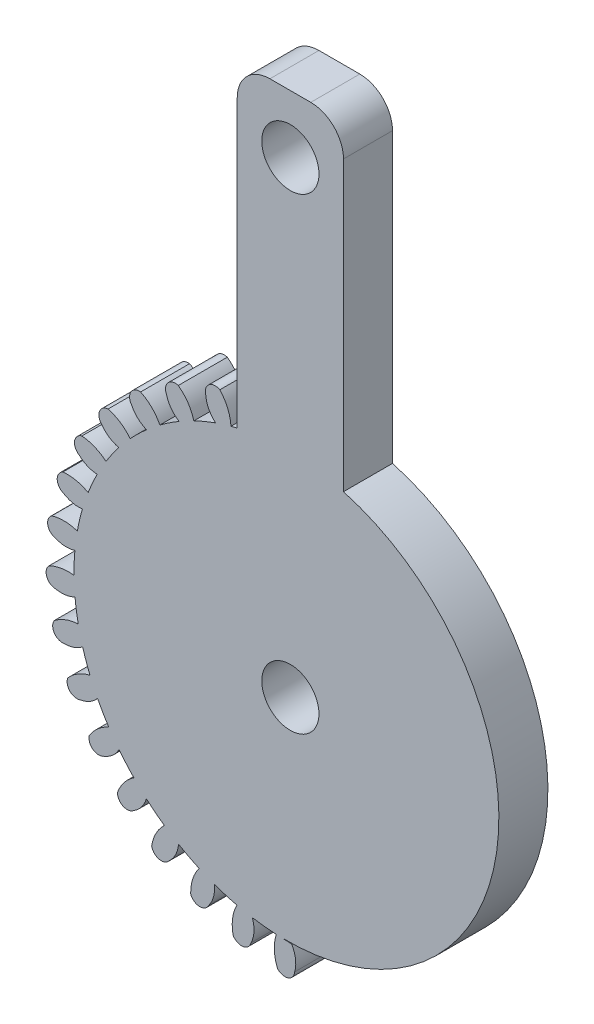
SolidWorks part; units mm, degrees
ref_plane "Front Plane" through (0, 0, 0) normal (0, 0, 1) x (1, 0, 0)
ref_plane "Top Plane" through (0, 0, 0) normal (0, 1, 0) x (1, 0, 0)
ref_plane "Right Plane" through (0, 0, 0) normal (1, 0, 0) x (0, 0, -1)
ref_plane "Plane1" through (0, 0, 5) normal (0, 0, 1) x (1, 0, 0)
ref_plane "Plane3" through (0, 0, 3) normal (0, 0, 1) x (1, 0, 0)
sketch "Sketch1" plane through (0, 0, 5) normal (0, 0, 1) x (1, 0, 0)
  circle A0 centre (0, 20.9252) radius 3.9726
  circle A1 centre (0, 20.9252) radius 5
  dimension "D1" = 10
sketch "Sketch5" plane through (0, 0, 3) normal (0, 0, 1) x (1, 0, 0)
  circle A0 centre (0, 20.9252) radius 13
extrude "Boss-Extrude3" add sketch "Sketch5" along normal blind 3 contours A0
sketch "Sketch6" plane through (0, 0, 3) normal (0, 0, 1) x (1, 0, 0)
  line L1 (-3.01, 33.0817) -> (3.49, 33.0817)
  line L2 (-3.01, 33.0817) -> (-3.01, 53.0817)
  line L3 (-3.01, 53.0817) -> (3.49, 53.0817)
  line L4 (3.49, 33.0817) -> (3.49, 53.0817)
  dimension "D1" = 20
  dimension "D2" = 6.5
extrude "Boss-Extrude4" add sketch "Sketch6" along normal up to surface (3 mm away) up to face at (13, 20.9252, 6)
sketch "Sketch8" plane through (0, 0, 3) normal (0, 0, 1) x (1, 0, 0)
  line L0 (-4.296, 33.1462) -> (-3.39, 33.4105)
  line L1 (0.24, 53.0817) -> (0.24, -3.388) construction
  line L2 (3.49, 53.0817) -> (-3.01, 53.0817) construction
  line L3 (13, 20.9252) -> (-7.0281, 20.9252) construction
  line L4 (-6.4797, 32.0955) -> (-5.6382, 32.5229)
  line L5 (-8.4311, 30.6587) -> (-7.6833, 31.2345)
  line L6 (-10.0829, 28.8855) -> (-9.4546, 29.5898)
  line L7 (-11.3779, 26.8373) -> (-10.8908, 27.6456)
  line L8 (-12.2715, 24.5847) -> (-11.9424, 25.4693)
  line L9 (-12.7326, 22.2057) -> (-12.573, 23.1358)
  line L10 (-12.7455, 19.7824) -> (-12.7607, 20.726)
  line L11 (-12.3095, 17.3986) -> (-12.4992, 18.3231)
  line L12 (-11.4399, 15.1367) -> (-11.7974, 16.0101)
  line L13 (-10.1667, 13.0748) -> (-10.6797, 13.867)
  line L14 (-8.5338, 11.2842) -> (-9.1845, 11.9678)
  line L15 (-6.5977, 9.8268) -> (-7.3637, 10.3781)
  line L16 (-4.4253, 8.753) -> (-5.2801, 9.1529)
  line L17 (-2.0916, 8.0998) -> (-3.0057, 8.3346)
  line L18 (0.3226, 7.8899) -> (-0.6192, 7.9514)
  arc A0 (-3.39, 33.4105) -> (-4.0758, 35.0663) centre (-5.9543, 33.3183) ccw
  arc A1 (-5.6382, 32.5229) -> (-6.6186, 34.0231) centre (-8.1411, 31.9576) ccw
  arc A2 (-4.0758, 35.0663) -> (-4.9399, 34.3825) centre (-4.3614, 34.5393) ccw
  arc A3 (-4.9399, 34.3825) -> (-4.296, 33.1462) centre (-3.1926, 34.5068) ccw
  arc A4 (-3.01, 33.572) -> (3.49, 33.448) centre (0, 20.9252) ccw construction
  arc A5 (-6.6186, 34.0231) -> (-7.3413, 33.1912) centre (-6.8018, 33.4524) ccw
  arc A6 (-7.3413, 33.1912) -> (-6.4797, 32.0955) centre (-5.6471, 33.6368) ccw
  arc A7 (-7.6833, 31.2345) -> (-8.9245, 32.5273) centre (-10.0383, 30.2157) ccw
  arc A8 (-8.9245, 32.5273) -> (-9.4806, 31.576) centre (-8.9988, 31.9325) ccw
  arc A9 (-9.4806, 31.576) -> (-8.4311, 30.6587) centre (-7.8982, 32.3274) ccw
  arc A10 (-9.4546, 29.5898) -> (-10.9136, 30.6305) centre (-11.5804, 28.1527) ccw
  arc A11 (-10.9136, 30.6305) -> (-11.2841, 29.5927) centre (-10.8765, 30.0323) ccw
  arc A12 (-11.2841, 29.5927) -> (-10.0829, 28.8855) centre (-9.8681, 30.6241) ccw
  arc A13 (-10.8908, 27.6456) -> (-12.5173, 28.3983) centre (-12.7139, 25.8399) ccw
  arc A14 (-12.5173, 28.3983) -> (-12.6892, 27.3099) centre (-12.3701, 27.8173) ccw
  arc A15 (-12.6892, 27.3099) -> (-11.3779, 26.8373) centre (-11.4887, 28.5855) ccw
  arc A16 (-11.9424, 25.4693) -> (-13.6801, 25.9079) centre (-13.3997, 23.3573) ccw
  arc A17 (-13.6801, 25.9079) -> (-13.6476, 24.8064) centre (-13.4279, 25.3641) ccw
  arc A18 (-13.6476, 24.8064) -> (-12.2715, 24.5847) centre (-12.7039, 26.2823) ccw
  arc A19 (-12.573, 23.1358) -> (-14.3618, 23.2453) centre (-13.6142, 20.7907) ccw
  arc A20 (-14.3618, 23.2453) -> (-14.126, 22.1688) centre (-14.0133, 22.7576) ccw
  arc A21 (-14.126, 22.1688) -> (-12.7326, 22.2057) centre (-13.4718, 23.7938) ccw
  arc A22 (-12.7607, 20.726) -> (-14.5389, 20.5025) centre (-13.3499, 18.2286) ccw
  arc A23 (-14.5389, 20.5025) -> (-14.1079, 19.4883) centre (-14.1062, 20.0877) ccw
  arc A24 (-14.1079, 19.4883) -> (-12.7455, 19.7824) centre (-13.7658, 21.2063) ccw
  arc A25 (-12.4992, 18.3231) -> (-14.2053, 17.7743) centre (-12.616, 15.7598) ccw
  arc A26 (-14.2053, 17.7743) -> (-13.5941, 16.8574) centre (-13.7033, 17.4468) ccw
  arc A27 (-13.5941, 16.8574) -> (-12.3095, 17.3986) centre (-13.5758, 18.609) ccw
  arc A28 (-11.7974, 16.0101) -> (-13.3725, 15.155) centre (-11.4377, 13.4695) ccw
  arc A29 (-13.3725, 15.155) -> (-12.6021, 14.3671) centre (-12.8185, 14.926) ccw
  arc A30 (-12.6021, 14.3671) -> (-11.4399, 15.1367) centre (-12.9084, 16.0918) ccw
  arc A31 (-10.6797, 13.867) -> (-12.0692, 12.7351) centre (-9.8559, 11.4368) ccw
  arc A32 (-12.0692, 12.7351) -> (-11.1663, 12.1034) centre (-11.4825, 12.6126) ccw
  arc A33 (-11.1663, 12.1034) -> (-10.1667, 13.0748) centre (-11.7865, 13.7417) ccw
  arc A34 (-9.1845, 11.9678) -> (-10.3406, 10.5982) centre (-7.9252, 9.7321) ccw
  arc A35 (-10.3406, 10.5982) -> (-9.3363, 10.1446) centre (-9.7413, 10.5865) ccw
  arc A36 (-9.3363, 10.1446) -> (-8.5338, 11.2842) centre (-10.2491, 11.6397) ccw
  arc A37 (-7.3637, 10.3781) -> (-8.2463, 8.8183) centre (-5.7123, 8.4142) ccw
  arc A38 (-8.2463, 8.8183) -> (-7.1754, 8.5583) centre (-7.6552, 8.9177) ccw
  arc A39 (-7.1754, 8.5583) -> (-6.5977, 9.8268) centre (-8.3491, 9.8587) ccw
  arc A40 (-5.2801, 9.1529) -> (-5.8587, 7.4567) centre (-3.2937, 7.5286) ccw
  arc A41 (-5.8587, 7.4567) -> (-4.7582, 7.3995) centre (-5.2962, 7.6638) ccw
  arc A42 (-4.7582, 7.3995) -> (-4.4253, 8.753) centre (-6.1524, 8.4601) ccw
  arc A43 (-3.0057, 8.3346) -> (-3.2603, 6.5606) centre (-0.753, 7.106) ccw
  arc A44 (-3.2603, 6.5606) -> (-2.1683, 6.7081) centre (-2.7459, 6.8682) ccw
  arc A45 (-2.1683, 6.7081) -> (-2.0916, 8.0998) centre (-3.7347, 7.4923) ccw
  arc A46 (-0.6192, 7.9514) -> (-0.541, 6.1609) centre (1.822, 7.161) ccw
  arc A47 (-0.541, 6.1609) -> (0.5049, 6.508) centre (-0.0924, 6.5585) ccw
  arc A48 (0.5049, 6.508) -> (0.3226, 7.8899) centre (-1.1796, 6.9887) ccw
  point P26 (0.24, 20.9252)
  point P153 (0.24, 20.9252)
  dimension "D1" = 16
extrude "Boss-Extrude5" add sketch "Sketch8" along normal up to surface (3 mm away) up to face at (0.118, 36.9003, 6)
sketch "Sketch9" plane through (0, 0, 3) normal (0, 0, -1) x (-1, 0, 0)
  line L0 (-0.24, 53.0817) -> (-0.24, 49.0919) construction
  line L1 (-3.49, 53.0817) -> (3.01, 53.0817) construction
  line L2 (-0.24, 47.7817) -> (-0.24, -3.3539) construction
  line L3 (-13, 20.9252) -> (46.8577, 20.9252) construction
  circle A0 centre (-0.24, 49.5317) radius 1.75
  arc A1 (-3.49, 33.448) -> (0.2579, 7.9278) centre (0, 20.9252) ccw construction
  circle A2 centre (-0.24, 20.9252) radius 1.75
  point P16 (-0.24, 20.9252)
  dimension "D1" = 3.55
extrude "Cut-Extrude1" cut sketch "Sketch9" against normal up to surface (3 mm away) up to face at (-8.1909, 20.6875, 6)
fillet "Fillet1" radius 2 2 edges at (3.49, 53.0817, 4.5) (-3.01, 53.0817, 4.5)
